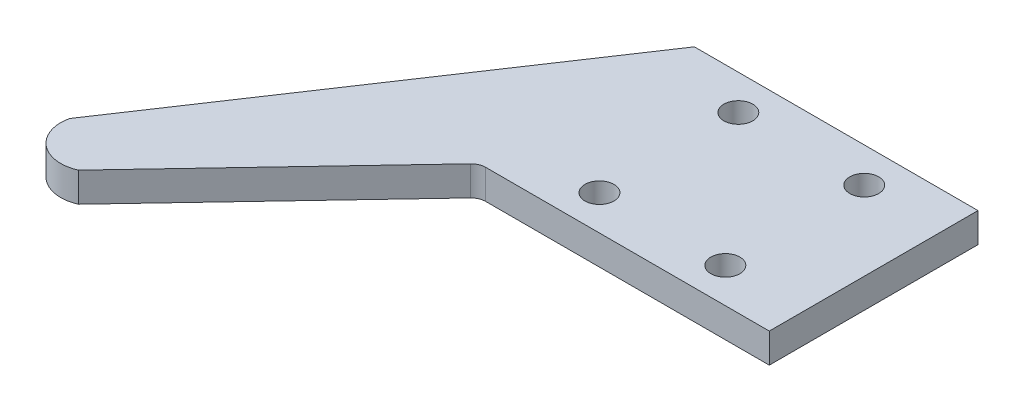
SolidWorks part; units mm, degrees
material "6061 Alloy"
ref_plane "Front Plane" through (0, 0, 0) normal (0, 0, 1) x (1, 0, 0)
ref_plane "Top Plane" through (0, 0, 0) normal (0, 1, 0) x (1, 0, 0)
ref_plane "Right Plane" through (0, 0, 0) normal (1, 0, 0) x (0, 0, -1)
sketch "Sketch1" plane through (0, 0, 0) normal (0, 1, 0) x (1, 0, 0)
  line L1 (27.2348, -40.223) -> (-5.4827, -74.8309)
  line L4 (77.8311, -3.5504) -> (77.8311, -39.4279)
  line L5 (77.8311, -39.4279) -> (29.0806, -39.4279)
  line L6 (77.8311, -3.5504) -> (29.0806, -3.5504)
  line L7 (29.0806, -3.5504) -> (-13.9431, -67.9117)
  arc A0 (-5.4827, -74.8309) -> (-13.9431, -67.9117) centre (-8.026, -69.3087) cw
  arc A2 (27.2348, -40.223) -> (29.0806, -39.4279) centre (29.0806, -41.9679) cw
  dimension "D1" = 2.54
  dimension "D3" = 47.625
extrude "Boss-Extrude1" add sketch "Sketch1" along normal blind 5.08
sketch "Sketch2" plane through (0, 5.08, 0) normal (0, 1, 0) x (1, 0, 0)
  line L0 (29.0806, -3.5504) -> (77.8311, -39.4279) construction
  line L1 (53.4558, -21.4892) -> (64.2762, -21.4892) construction
  line L3 (64.2762, -21.4892) -> (64.2762, -9.5512) construction
  line L6 (64.2762, -21.4892) -> (64.2762, -33.4272) construction
  line L7 (53.4558, -21.4892) -> (42.6354, -21.4892) construction
  line L8 (42.6354, -21.4892) -> (42.6354, -9.5512) construction
  line L9 (42.6354, -21.4892) -> (42.6354, -33.4272) construction
  line L10 (53.4558, -21.4892) -> (53.4558, -3.5504) construction
  line L11 (77.8311, -3.5504) -> (29.0806, -3.5504) construction
  dimension "D1" = 21.6408
  dimension "D2" = 23.876
  dimension "D3" = 23.876
hole_wizard "#10 Clearance Hole1" positions "Sketch3" profile "Sketch4" hole size "#10" standard "ANSI Inch" end condition through all
sketch "Sketch3" plane through (0, 5.08, 0) normal (0, 1, 0) x (1, 0, 0)
  point P0 (42.6354, -33.4272)
  point P3 (42.6354, -9.5512)
  point P6 (64.2762, -9.5512)
  point P9 (64.2762, -33.4272)
sketch "Sketch4" plane through (42.6354, 5.08, 33.4272) normal (1, 0, 0) x (0, 0, 1)
  line L0 (0, 0) -> (0, 5.08)
  line L1 (0, 5.08) -> (2.4892, 5.08)
  line L2 (2.4892, 5.08) -> (2.4892, 0)
  line L5 (2.4892, 0) -> (0, 0)
  line L11 (0, -6.35) -> (0, 107.95) construction
  dimension "Thru Hole Dia." = 4.9784
  dimension "Thru Hole Depth" = 5.08
